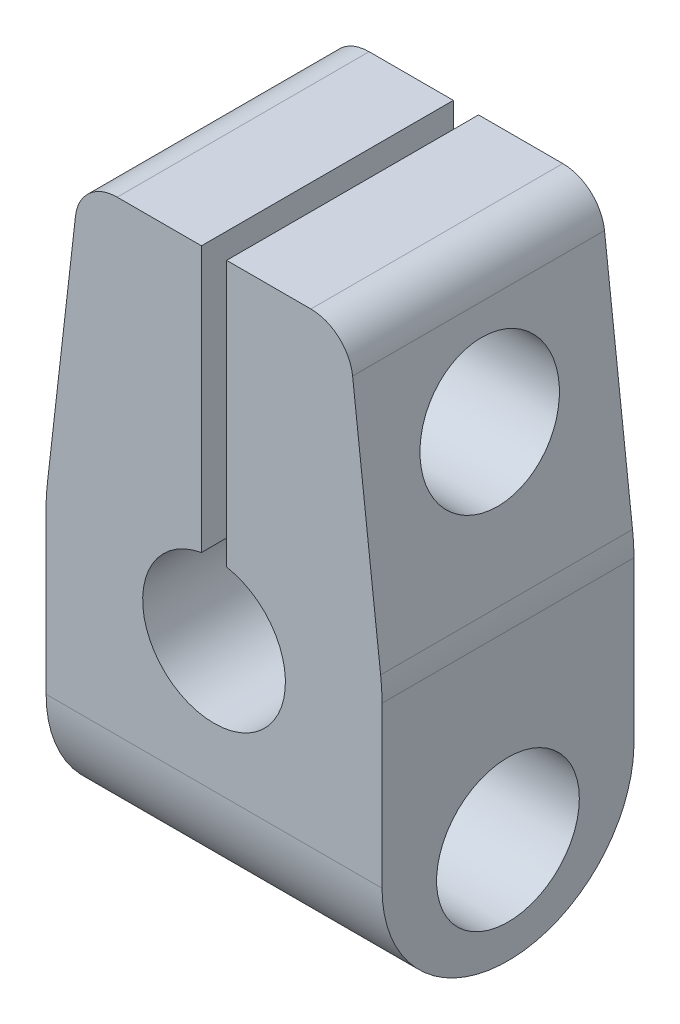
SolidWorks part; units mm, degrees
ref_plane "前视基准面" through (0, 0, 0) normal (0, 0, 1) x (1, 0, 0)
ref_plane "上视基准面" through (0, 0, 0) normal (0, 1, 0) x (1, 0, 0)
ref_plane "右视基准面" through (0, 0, 0) normal (1, 0, 0) x (0, 0, -1)
sketch "草图1" plane through (0, 0, 0) normal (0, 0, 1) x (1, 0, 0)
  line L0 (0, 7.4737) -> (0, -6.8567) construction
  line L1 (-3.5, -7) -> (3.5, -7)
  line L2 (4, -6.5) -> (4, 0.7147)
  line L3 (3.9675, 1.2835) -> (3.3, 7.1138)
  line L4 (2.3065, 8) -> (0.3, 8)
  line L5 (-4, -6.5) -> (-4, 0.7147)
  line L6 (-3.9675, 1.2835) -> (-3.3, 7.1138)
  line L7 (-0.3, 8) -> (-0.3, 1.6733)
  line L8 (0.3, 8) -> (0.3, 1.6733)
  line L9 (-0.3, 8) -> (-2.3065, 8)
  arc A0 (-0.3, 1.6733) -> (0.3, 1.6733) centre (0, 0) ccw
  arc A1 (3.5, -7) -> (4, -6.5) centre (3.5, -6.5) ccw
  arc A2 (4, 0.7147) -> (3.9675, 1.2835) centre (-1, 0.7147) ccw
  arc A3 (3.3, 7.1138) -> (2.3065, 8) centre (2.3065, 7) ccw
  arc A4 (-3.5, -7) -> (-4, -6.5) centre (-3.5, -6.5) cw
  arc A5 (-4, 0.7147) -> (-3.9675, 1.2835) centre (1, 0.7147) cw
  arc A6 (-3.3, 7.1138) -> (-2.3065, 8) centre (-2.3065, 7) cw
  point P12 (4, -7)
  point P15 (4, 1)
  point P19 (0, -7)
  point P27 (0, 5)
  dimension "D1" = 3.4
  dimension "D6" = 0.5
  dimension "D7" = 5
  dimension "D8" = 1
  dimension "D2" = 7
  dimension "D3" = 8
  dimension "D4" = 8
  dimension "D5" = 4
  dimension "D9" = 0.3
  dimension "D10" = 3
extrude "凸台-拉伸1" add sketch "草图1" along normal blind 6
sketch "草图2" plane through (4, 0, 0) normal (1, 0, 0) x (0, 0, -1)
  line L0 (-3, 3.3232) -> (-3, -5.6434) construction
  line L1 (1.9466, -3.6) -> (-9.6678, -3.6) construction
  line L2 (-6, -7) -> (0, -7) construction
  circle A0 centre (-3, -3.6) radius 1.7
  dimension "D2" = 3.4
  dimension "D1" = 3.4
extrude "切除-拉伸1" cut sketch "草图2" against normal through all
sketch "草图3" plane through (0, 0, 0) normal (1, 0, 0) x (0, 0, -1)
  line L0 (-3, 7.112) -> (-3, -10.0911) construction
  line L1 (3.4167, 4.8) -> (-11.8085, 4.8) construction
  line L2 (-6, 8) -> (0, 8) construction
  circle A0 centre (-3, 4.8) radius 1.65
  dimension "D2" = 3.3
  dimension "D1" = 3.2
extrude "切除-拉伸2" cut sketch "草图3" against normal through all both and the other way through all
sketch "草图4" plane through (-4, 0, 0) normal (-1, 0, 0) x (0, 0, 1)
  line L0 (7.1376, -3.6) -> (-2.4973, -3.6) construction
  line L1 (2.9991, -8.8228) -> (2.9991, 0.3385) construction
  line L2 (0, -3.1728) -> (0, -9.013)
  line L6 (0, -9.013) -> (5.9991, -9.013)
  line L8 (5.9991, -3.1) -> (6.0942, -3.1)
  line L9 (6.0942, -3.1) -> (6.0942, -9.013)
  line L10 (6.0942, -9.013) -> (5.9991, -9.013)
  arc A1 (0, -3.1728) -> (5.9991, -3.1) centre (2.9991, -3.1) ccw
  dimension "D1" = 6
  dimension "D2" = 0.5
extrude "切除-拉伸3" cut sketch "草图4" against normal up to next
